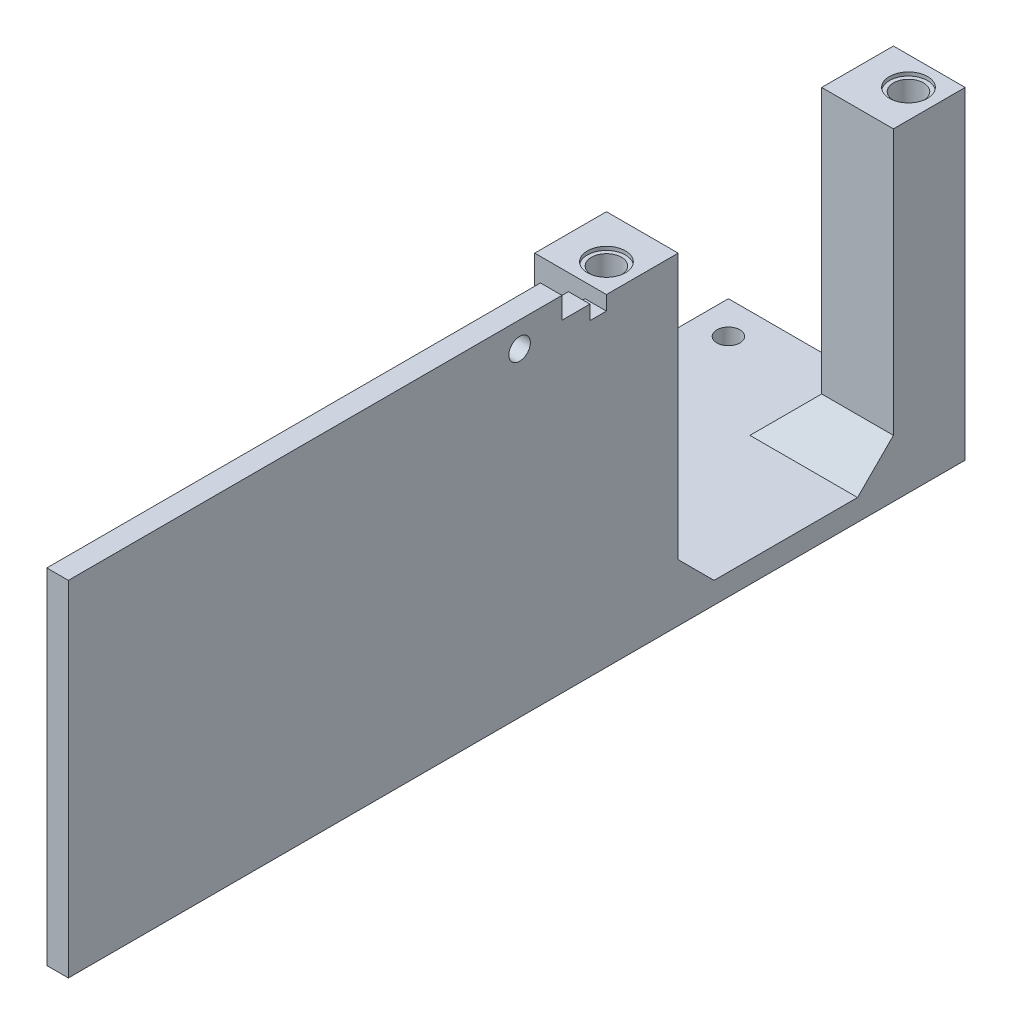
SolidWorks part; units mm, degrees
ref_plane "Front Plane" through (0, 0, 0) normal (0, 0, 1) x (1, 0, 0)
ref_plane "Top Plane" through (0, 0, 0) normal (0, 1, 0) x (1, 0, 0)
ref_plane "Right Plane" through (0, 0, 0) normal (1, 0, 0) x (0, 0, -1)
sketch "Sketch1" plane through (0, 0, 0) normal (0, 1, 0) x (1, 0, 0)
  line L1 (-6.5124, 9.686) -> (1.4876, 9.686)
  line L2 (-6.5124, 9.686) -> (-6.5124, -40.314)
  line L3 (-6.5124, -40.314) -> (1.4876, -40.314)
  line L4 (1.4876, 9.686) -> (1.4876, -40.314)
  line L5 (1.4876, 9.686) -> (26.4876, 9.686)
  line L6 (1.4876, 9.686) -> (1.4876, -40.314)
  line L7 (1.4876, -40.314) -> (26.4876, -40.314)
  line L8 (26.4876, 9.686) -> (26.4876, -40.314)
  circle A0 centre (-1.9624, -35.764) radius 1.6
  circle A1 centre (-1.9624, 5.136) radius 1.6
  dimension "D4" = 3.2
  dimension "D5" = 3.2
  dimension "D6" = 4.55
  dimension "D7" = 4.55
  dimension "D8" = 4.55
  dimension "D9" = 4.55
  dimension "D1" = 8
  dimension "D2" = 50
  dimension "D3" = 25
extrude "Boss-Extrude1" add sketch "Sketch1" along normal blind 3 contours A1 | A0 | L5 L8 L7 L3 L2 L1
sketch "Sketch2" plane through (0, 3, 0) normal (0, 1, 0) x (1, 0, 0)
  line L1 (26.4876, -40.314) -> (16.4876, -40.314)
  line L2 (26.4876, -40.314) -> (26.4876, -30.314)
  line L3 (26.4876, -30.314) -> (16.4876, -30.314)
  line L4 (16.4876, -40.314) -> (16.4876, -30.314)
  line L5 (26.4876, 9.686) -> (16.4876, 9.686)
  line L6 (26.4876, 9.686) -> (26.4876, -0.314)
  line L7 (26.4876, -0.314) -> (16.4876, -0.314)
  line L8 (16.4876, 9.686) -> (16.4876, -0.314)
  dimension "D1" = 10
  dimension "D2" = 10
  dimension "D3" = 10
  dimension "D4" = 10
extrude "Boss-Extrude2" add sketch "Sketch2" along normal blind 42
chamfer "Chamfer1" distance 5 angle 45 4 edges at (16.4876, 3, -4.686) (21.4876, 3, 0.314) (16.4876, 3, 35.314) (21.4876, 3, 30.314)
ref_plane "Plane1" through (0, 45, 0) normal (0, 1, 0) x (1, 0, 0)
sketch "Sketch3" plane through (0, 45, 0) normal (0, 1, 0) x (1, 0, 0)
  line L0 (26.4876, -40.314) -> (26.4876, -30.314) construction
  line L1 (16.4876, -40.314) -> (26.4876, -40.314) construction
  line L2 (26.4876, -0.314) -> (26.4876, 9.686) construction
  line L3 (26.4876, 9.686) -> (16.4876, 9.686) construction
  circle A0 centre (22.5376, -36.364) radius 2.1
  circle A1 centre (22.5376, 5.736) radius 2.1
  dimension "D1" = 4.2
  dimension "D3" = 3.95
  dimension "D4" = 4.2
  dimension "D6" = 3.95
  dimension "D2" = 3.95
  dimension "D5" = 3.95
extrude "Cut-Extrude1" cut sketch "Sketch3" against normal blind 52
sketch "Sketch4" plane through (0, 45, 0) normal (0, 1, 0) x (1, 0, 0)
  circle A0 centre (22.5376, -36.364) radius 2.65
  circle A1 centre (22.5376, 5.736) radius 2.65
  dimension "D1" = 5.3
  dimension "D2" = 5.3
extrude "Cut-Extrude2" cut sketch "Sketch4" against normal blind 0.5
ref_plane "Plane2" through (0, 22.5, 0) normal (0, -1, 0) x (-1, 0, 0)
mirror "Mirror1" about plane through (0, 22.5, 0) normal (0, -1, 0) of "Cut-Extrude2"
sketch "Sketch5" plane through (0, 0, 40.314) normal (0, 0, 1) x (1, 0, 0)
  line L0 (26.4876, 45) -> (26.4876, 0) construction
  line L1 (26.4876, 43) -> (23.4876, 43)
  line L2 (26.4876, 43) -> (26.4876, 0)
  line L3 (26.4876, 0) -> (23.4876, 0)
  line L4 (23.4876, 43) -> (23.4876, 0)
  line L5 (-6.5124, 0) -> (26.4876, 0) construction
  line L6 (16.4876, 45) -> (26.4876, 45) construction
  dimension "D1" = 3
  dimension "D2" = 2
extrude "Boss-Extrude3" add sketch "Sketch5" along normal blind 75
sketch "Sketch6" plane through (0, 43, 0) normal (0, 1, 0) x (1, 0, 0)
  line L0 (23.4876, -115.314) -> (23.4876, -40.314) construction
  line L1 (23.4876, -42.614) -> (26.4876, -42.614)
  line L2 (23.4876, -42.614) -> (23.4876, -46.514)
  line L3 (23.4876, -46.514) -> (26.4876, -46.514)
  line L4 (26.4876, -42.614) -> (26.4876, -46.514)
  line L5 (26.4876, -115.314) -> (26.4876, -40.314) construction
  line L6 (16.4876, -40.314) -> (26.4876, -40.314) construction
  dimension "D1" = 2.3
  dimension "D2" = 3.9
extrude "Boss-Extrude4" add sketch "Sketch6" along normal up to surface (2 mm away) up to face at (22.5376, 45, 39.014)
sketch "Sketch7" plane through (0, 43, 0) normal (0, 1, 0) x (1, 0, 0)
  line L1 (23.4876, -115.314) -> (26.4876, -115.314)
  line L2 (23.4876, -115.314) -> (23.4876, -46.514)
  line L3 (23.4876, -46.514) -> (26.4876, -46.514)
  line L4 (26.4876, -115.314) -> (26.4876, -46.514)
extrude "Boss-Extrude5" add sketch "Sketch7" along normal blind 5
sketch "Sketch8" plane through (23.4876, 0, 0) normal (-1, 0, 0) x (0, 0, 1)
  circle A0 centre (52.414, 44.5) radius 1.5
  dimension "D1" = 3
extrude "Cut-Extrude3" cut sketch "Sketch8" against normal blind 5
